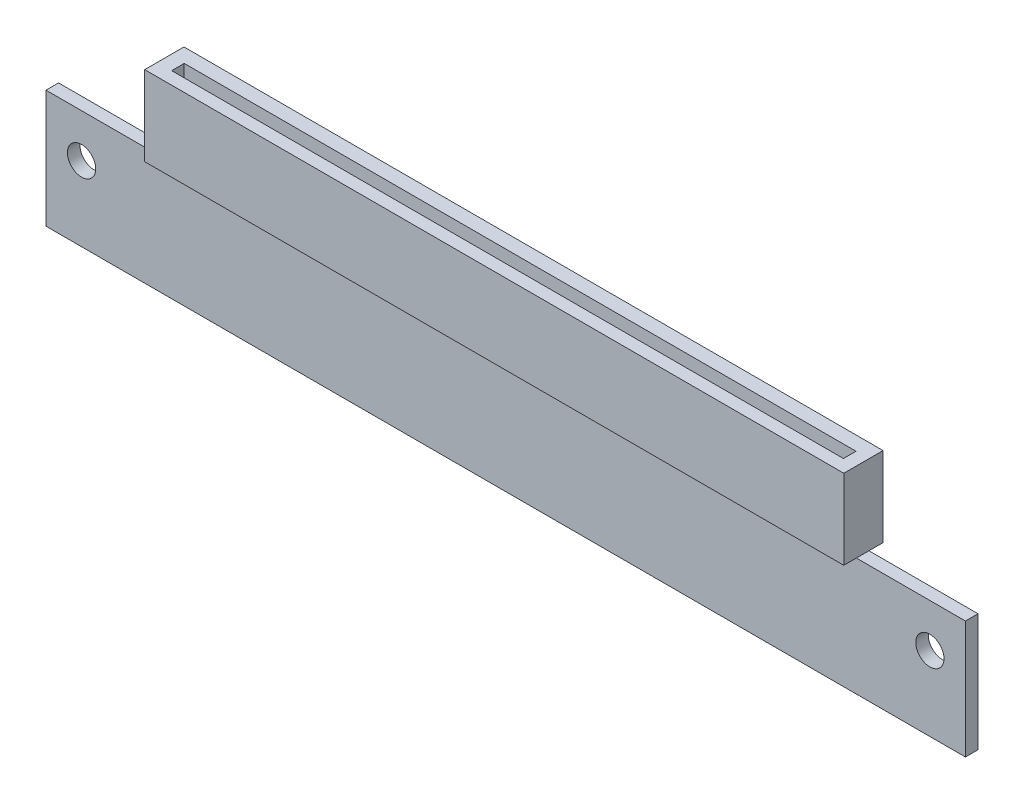
SolidWorks part; units mm, degrees
ref_plane "Front Plane" through (0, 0, 0) normal (0, 0, 1) x (1, 0, 0)
ref_plane "Top Plane" through (0, 0, 0) normal (0, 1, 0) x (1, 0, 0)
ref_plane "Right Plane" through (0, 0, 0) normal (1, 0, 0) x (0, 0, -1)
sketch "Sketch1" plane through (0, 0, 0) normal (0, 1, 0) x (1, 0, 0)
  line L1 (-44.5, 2.5) -> (44.5, 2.5)
  line L2 (-44.5, 2.5) -> (-44.5, -2.5)
  line L3 (-44.5, -2.5) -> (44.5, -2.5)
  line L4 (44.5, 2.5) -> (44.5, -2.5)
  line L5 (-44.5, 2.5) -> (44.5, -2.5) construction
  line L6 (-44.5, -2.5) -> (44.5, 2.5) construction
  point P0 (0, 0)
  dimension "D1" = 89
  dimension "D2" = 5
extrude "Boss-Extrude1" add sketch "Sketch1" along normal blind 10.1494
sketch "Sketch2" plane through (0, 10.1494, 0) normal (0, 1, 0) x (1, 0, 0)
  line L0 (-44.5, 2.5) -> (-44.5, -2.5) construction
  line L1 (-42.6723, 0.7024) -> (42.8547, 0.7024)
  line L2 (-42.6723, 0.7024) -> (-42.6723, -0.8976)
  line L3 (-42.6723, -0.8976) -> (42.8547, -0.8976)
  line L4 (42.8547, 0.7024) -> (42.8547, -0.8976)
  line L5 (-42.6723, 0.7024) -> (42.8547, -0.8976) construction
  line L6 (-42.6723, -0.8976) -> (42.8547, 0.7024) construction
  point P0 (0.0912, -0.0976)
  dimension "D1" = 1.6
  dimension "D2" = 1.8277
  dimension "D3" = 85.527
extrude "Cut-Extrude1" cut sketch "Sketch2" against normal blind 7.7558
sketch "Sketch3" plane through (0, 0, 0) normal (0, -1, 0) x (1, 0, 0)
  line L0 (-42.6723, 0.8976) -> (42.8547, 0.8976) construction
  line L1 (-58.668, 0.8976) -> (58.3836, 0.8976)
  line L2 (-58.668, 0.8976) -> (-58.668, -0.7024)
  line L3 (-58.668, -0.7024) -> (58.3836, -0.7024)
  line L4 (58.3836, 0.8976) -> (58.3836, -0.7024)
  line L5 (-58.668, 0.8976) -> (58.3836, -0.7024) construction
  line L6 (-58.668, -0.7024) -> (58.3836, 0.8976) construction
  line L7 (-44.5, -2.5) -> (-44.5, 2.5) construction
  point P0 (-0.1422, 0.0976)
  dimension "D1" = 117.0516
  dimension "D2" = 1.6
  dimension "D3" = 14.168
extrude "Boss-Extrude2" add sketch "Sketch3" along normal blind 15 contours L2 L1 L4 L3
hole_wizard "M3 Clearance Hole1" positions "Sketch4" profile "Sketch5" hole size "M3" standard "AS" end condition up to next
sketch "Sketch4" plane through (0, 0, 0.8976) normal (0, 0, 1) x (1, 0, 0)
  line L0 (-58.668, 0) -> (-44.5, 0) construction
  line L1 (-58.668, -15) -> (-58.668, 0) construction
  line L2 (58.3836, -15) -> (58.3836, 0) construction
  point P0 (-54.1422, -5.5258)
  point P2 (53.8578, -5.5258)
  point P11 (0, 0)
  dimension "D1" = 5.5258
  dimension "D2" = 4.5258
  dimension "D3" = 4.5258
sketch "Sketch5" plane through (-54.1422, -5.5258, 0.8976) normal (1, 0, 0) x (0, -1, 0)
  line L0 (0, 0) -> (0, 1.6)
  line L1 (0, 1.6) -> (1.8, 1.6)
  line L2 (1.8, 1.6) -> (1.8, 0)
  line L5 (1.8, 0) -> (0, 0)
  line L11 (0, -6.35) -> (0, 107.95) construction
  dimension "Thru Hole Dia." = 3.6
  dimension "Thru Hole Depth" = 1.6
